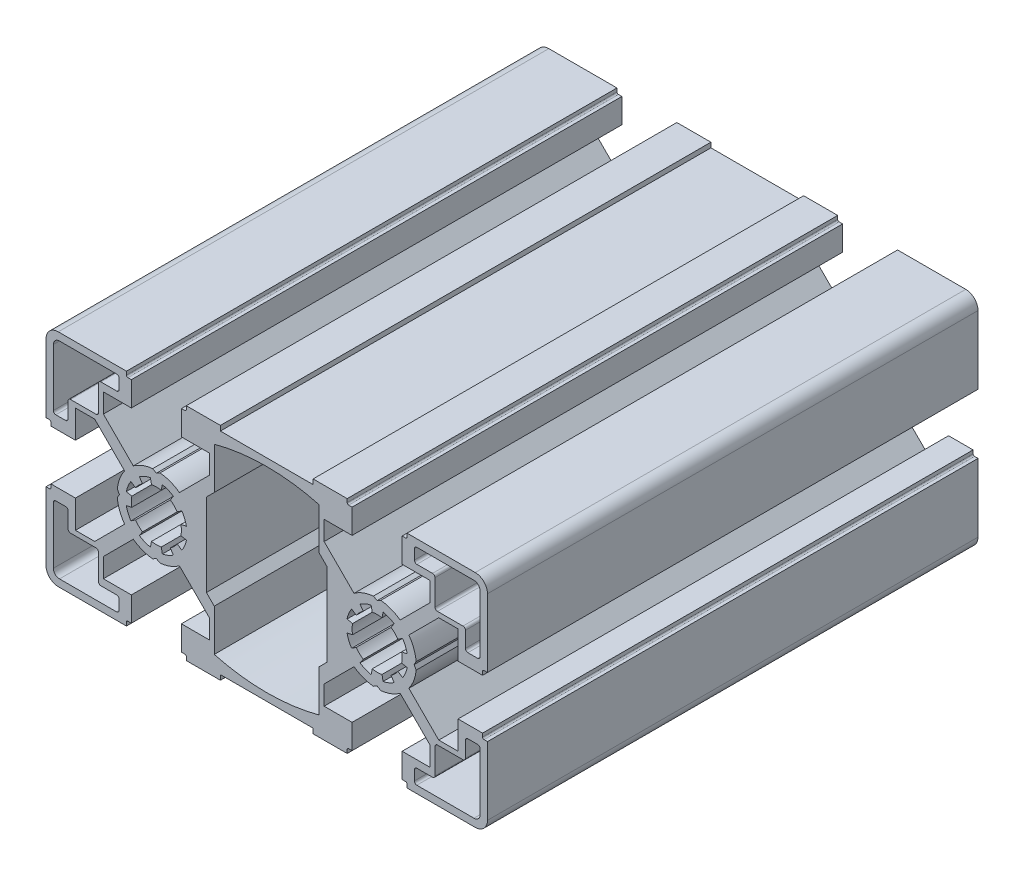
SolidWorks part; units mm, degrees
ref_plane "前视基准面" through (0, 0, 0) normal (0, 0, 1) x (1, 0, 0)
ref_plane "上视基准面" through (0, 0, 0) normal (0, 1, 0) x (1, 0, 0)
ref_plane "右视基准面" through (0, 0, 0) normal (1, 0, 0) x (0, 0, -1)
sketch "草图1" plane through (0, 0, 0) normal (0, 0, 1) x (1, 0, 0)
  line L0 (-29.0828, 22.0458) -> (-42.9828, 22.0458)
  line L1 (-45.4828, 19.5458) -> (-45.4828, 5.6458)
  line L2 (-28.0828, 16.0458) -> (-33.7828, 16.0458)
  line L3 (-39.4828, 10.3458) -> (-39.4828, 4.6458)
  line L4 (-43.4828, 7.1458) -> (-41.4828, 7.1458)
  line L5 (-40.9828, 7.6458) -> (-40.9828, 10.8458)
  line L6 (-40.4828, 11.3458) -> (-35.2828, 11.3458)
  line L7 (-34.7828, 11.8458) -> (-34.7828, 17.0458)
  line L8 (-34.2828, 17.5458) -> (-31.0828, 17.5458)
  line L9 (-30.5828, 18.0458) -> (-30.5828, 20.0458)
  line L10 (-31.0828, 20.5458) -> (-42.7328, 20.5458)
  line L11 (-43.9828, 19.2958) -> (-43.9828, 7.6458)
  line L12 (-28.0828, 21.0458) -> (-28.7828, 21.0458)
  line L13 (-29.0828, 21.3458) -> (-29.0828, 22.0458)
  line L14 (-45.4828, 5.6458) -> (-44.7828, 5.6458)
  line L15 (-44.4828, 5.3458) -> (-44.4828, 4.6458)
  line L16 (-39.4828, 10.3458) -> (-35.5506, 10.3458)
  line L17 (-44.4828, 4.6458) -> (-42.5828, 4.6458)
  line L18 (-41.3828, 4.6458) -> (-39.4828, 4.6458)
  line L19 (-33.7828, 16.0458) -> (-33.7828, 12.1136)
  line L20 (-28.0828, 21.0458) -> (-28.0828, 19.1458)
  line L21 (-28.0828, 17.9458) -> (-28.0828, 16.0458)
  line L22 (-35.5506, 10.3458) -> (-29.4541, 4.2493)
  line L23 (-33.7828, 12.1136) -> (-27.6863, 6.0171)
  line L24 (-16.8828, 22.0458) -> (-9.9328, 22.0458)
  line L25 (-9.9328, 21.0458) -> (8.9672, 21.0458)
  line L26 (-17.8828, 16.0458) -> (-12.1828, 16.0458)
  line L27 (-17.8828, 21.0458) -> (-17.1828, 21.0458)
  line L28 (-16.8828, 21.3458) -> (-16.8828, 22.0458)
  line L29 (-12.1828, 16.0458) -> (-12.1828, 12.1136)
  line L30 (-11.1828, 9.578) -> (-12.7828, 7.978)
  line L31 (-12.1828, 12.1136) -> (-18.2793, 6.0171)
  line L32 (-17.8828, 21.0458) -> (-17.8828, 19.1458)
  line L33 (-17.8828, 17.6208) -> (-17.8828, 16.0458)
  line L34 (-29.0828, -22.9542) -> (-42.9828, -22.9542)
  line L35 (-45.4828, -20.4542) -> (-45.4828, -6.5542)
  line L36 (-28.0828, -16.9542) -> (-33.7828, -16.9542)
  line L37 (-39.4828, -11.2542) -> (-39.4828, -5.5542)
  line L38 (-43.4828, -8.0542) -> (-41.4828, -8.0542)
  line L39 (-40.9828, -8.5542) -> (-40.9828, -11.7542)
  line L40 (-40.4828, -12.2542) -> (-35.2828, -12.2542)
  line L41 (-34.7828, -12.7542) -> (-34.7828, -17.9542)
  line L42 (-34.2828, -18.4542) -> (-31.0828, -18.4542)
  line L43 (-30.5828, -18.9542) -> (-30.5828, -20.9542)
  line L44 (-31.0828, -21.4542) -> (-42.7328, -21.4542)
  line L45 (-43.9828, -20.2042) -> (-43.9828, -8.5542)
  line L46 (-28.0828, -21.9542) -> (-28.7828, -21.9542)
  line L47 (-29.0828, -22.2542) -> (-29.0828, -22.9542)
  line L48 (-45.4828, -6.5542) -> (-44.7828, -6.5542)
  line L49 (-44.4828, -6.2542) -> (-44.4828, -5.5542)
  line L50 (-39.4828, -11.2542) -> (-35.5506, -11.2542)
  line L51 (-44.4828, -5.5542) -> (-42.5828, -5.5542)
  line L52 (-41.3828, -5.5542) -> (-39.4828, -5.5542)
  line L53 (-33.7828, -16.9542) -> (-33.7828, -13.022)
  line L54 (-28.0828, -21.9542) -> (-28.0828, -20.0542)
  line L55 (-28.0828, -18.8542) -> (-28.0828, -16.9542)
  line L56 (-35.5506, -11.2542) -> (-29.4541, -5.1577)
  line L57 (-33.7828, -13.022) -> (-27.6863, -6.9255)
  line L58 (-17.8828, -16.9542) -> (-12.1828, -16.9542)
  line L59 (-17.8828, -21.9542) -> (-17.1828, -21.9542)
  line L60 (-16.8828, -22.2542) -> (-16.8828, -22.9542)
  line L61 (-12.1828, -16.9542) -> (-12.1828, -13.022)
  line L62 (-11.1828, -10.4864) -> (-12.7828, -8.8864)
  line L63 (-12.1828, -13.022) -> (-18.2793, -6.9255)
  line L64 (-17.8828, -21.9542) -> (-17.8828, -20.0542)
  line L65 (-17.8828, -18.8542) -> (-17.8828, -16.9542)
  line L66 (-26.4551, -5.6509) -> (-25.8162, -4.6947)
  line L67 (-24.2021, -6.5841) -> (-23.9778, -5.4562)
  line L68 (-21.7635, -6.5841) -> (-21.9878, -5.4562)
  line L69 (-19.5105, -5.6509) -> (-20.1494, -4.6947)
  line L70 (-17.7861, -3.9265) -> (-18.7423, -3.2876)
  line L71 (-16.8529, -1.6735) -> (-17.9808, -1.4492)
  line L72 (-16.8529, 0.7651) -> (-17.9808, 0.5408)
  line L73 (-17.7861, 3.0181) -> (-18.7423, 2.3792)
  line L74 (-19.5105, 4.7425) -> (-20.1494, 3.7863)
  line L75 (-21.7635, 5.6757) -> (-21.9878, 4.5478)
  line L76 (-24.2021, 5.6757) -> (-23.9778, 4.5478)
  line L77 (-26.4551, 4.7425) -> (-25.8162, 3.7863)
  line L78 (-28.1795, 3.0181) -> (-27.2233, 2.3792)
  line L79 (-29.1127, 0.7651) -> (-27.9848, 0.5408)
  line L80 (-29.1127, -1.6735) -> (-27.9848, -1.4492)
  line L81 (-28.1795, -3.9265) -> (-27.2233, -3.2876)
  line L82 (-22.9828, 7.0775) -> (-22.2328, 7.5106)
  line L83 (-22.9828, 7.0775) -> (-23.7328, 7.5106)
  line L84 (-22.9828, -7.986) -> (-22.2328, -8.419)
  line L85 (-22.9828, -7.986) -> (-23.7328, -8.419)
  line L86 (-30.5146, -0.4542) -> (-30.9476, -1.2042)
  line L87 (-30.5146, -0.4542) -> (-30.9476, 0.2958)
  line L88 (15.9172, 22.0458) -> (8.9672, 22.0458)
  line L89 (16.9172, 16.0458) -> (11.2172, 16.0458)
  line L90 (16.9172, 21.0458) -> (16.2172, 21.0458)
  line L91 (15.9172, 21.3458) -> (15.9172, 22.0458)
  line L92 (11.2172, 16.0458) -> (11.2172, 12.1136)
  line L93 (16.9172, 21.0458) -> (16.9172, 19.1458)
  line L94 (16.9172, 17.9458) -> (16.9172, 16.0458)
  line L95 (10.2172, 9.578) -> (11.8172, 7.978)
  line L96 (11.2172, 12.1136) -> (17.3137, 6.0171)
  line L97 (28.1172, 22.0458) -> (42.0172, 22.0458)
  line L98 (44.5172, 19.5458) -> (44.5172, 5.6458)
  line L99 (27.1172, 16.0458) -> (32.8172, 16.0458)
  line L100 (38.5172, 10.3458) -> (38.5172, 4.6458)
  line L101 (42.5172, 7.1458) -> (40.5172, 7.1458)
  line L102 (40.0172, 7.6458) -> (40.0172, 10.8458)
  line L103 (39.5172, 11.3458) -> (34.3172, 11.3458)
  line L104 (33.8172, 11.8458) -> (33.8172, 17.0458)
  line L105 (33.3172, 17.5458) -> (30.1172, 17.5458)
  line L106 (29.6172, 18.0458) -> (29.6172, 20.0458)
  line L107 (30.1172, 20.5458) -> (41.7672, 20.5458)
  line L108 (43.0172, 19.2958) -> (43.0172, 7.6458)
  line L109 (27.1172, 21.0458) -> (27.8172, 21.0458)
  line L110 (28.1172, 21.3458) -> (28.1172, 22.0458)
  line L111 (44.5172, 5.6458) -> (43.8172, 5.6458)
  line L112 (43.5172, 5.3458) -> (43.5172, 4.6458)
  line L113 (38.5172, 10.3458) -> (34.585, 10.3458)
  line L114 (43.5172, 4.6458) -> (41.6172, 4.6458)
  line L115 (40.4172, 4.6458) -> (38.5172, 4.6458)
  line L116 (32.8172, 16.0458) -> (32.8172, 12.1136)
  line L117 (34.585, 10.3458) -> (28.4884, 4.2493)
  line L118 (32.8172, 12.1136) -> (26.7207, 6.0171)
  line L119 (27.1172, 21.0458) -> (27.1172, 19.1458)
  line L120 (27.1172, 17.9458) -> (27.1172, 16.0458)
  line L121 (16.9172, -16.9542) -> (11.2172, -16.9542)
  line L122 (16.9172, -21.9542) -> (16.2172, -21.9542)
  line L123 (15.9172, -22.2542) -> (15.9172, -22.9542)
  line L124 (11.2172, -16.9542) -> (11.2172, -13.022)
  line L125 (16.9172, -21.9542) -> (16.9172, -20.0542)
  line L126 (16.9172, -18.8542) -> (16.9172, -16.9542)
  line L127 (10.2172, -10.4864) -> (11.8172, -8.8864)
  line L128 (11.2172, -13.022) -> (17.3137, -6.9255)
  line L129 (28.1172, -22.9542) -> (42.0172, -22.9542)
  line L130 (44.5172, -20.4542) -> (44.5172, -6.5542)
  line L131 (27.1172, -16.9542) -> (32.8172, -16.9542)
  line L132 (38.5172, -11.2542) -> (38.5172, -5.5542)
  line L133 (40.0172, -8.5542) -> (40.0172, -11.7542)
  line L134 (39.5172, -12.2542) -> (34.3172, -12.2542)
  line L135 (33.8172, -12.7542) -> (33.8172, -17.9542)
  line L136 (33.3172, -18.4542) -> (30.1172, -18.4542)
  line L137 (29.6172, -18.9542) -> (29.6172, -20.9542)
  line L138 (30.1172, -21.4542) -> (41.7672, -21.4542)
  line L139 (43.0172, -20.2042) -> (43.0172, -8.5542)
  line L140 (27.1172, -21.9542) -> (27.8172, -21.9542)
  line L141 (28.1172, -22.2542) -> (28.1172, -22.9542)
  line L142 (44.5172, -6.5542) -> (43.8172, -6.5542)
  line L143 (43.5172, -6.2542) -> (43.5172, -5.5542)
  line L144 (38.5172, -11.2542) -> (34.585, -11.2542)
  line L145 (43.5172, -5.5542) -> (41.6172, -5.5542)
  line L146 (40.4172, -5.5542) -> (38.5172, -5.5542)
  line L147 (32.8172, -16.9542) -> (32.8172, -13.022)
  line L148 (34.585, -11.2542) -> (28.4884, -5.1577)
  line L149 (32.8172, -13.022) -> (26.7207, -6.9255)
  line L150 (27.1172, -21.9542) -> (27.1172, -20.0542)
  line L151 (27.1172, -18.8542) -> (27.1172, -16.9542)
  line L152 (18.5449, -5.6509) -> (19.1838, -4.6947)
  line L153 (20.7979, -6.5841) -> (21.0222, -5.4562)
  line L154 (23.2365, -6.5841) -> (23.0122, -5.4562)
  line L155 (25.4895, -5.6509) -> (24.8506, -4.6947)
  line L156 (27.2139, -3.9265) -> (26.2577, -3.2876)
  line L157 (28.1471, -1.6735) -> (27.0192, -1.4492)
  line L158 (28.1471, 0.7651) -> (27.0192, 0.5408)
  line L159 (27.2139, 3.0181) -> (26.2577, 2.3792)
  line L160 (25.4895, 4.7425) -> (24.8506, 3.7863)
  line L161 (23.2365, 5.6757) -> (23.0122, 4.5478)
  line L162 (20.7979, 5.6757) -> (21.0222, 4.5478)
  line L163 (18.5449, 4.7425) -> (19.1838, 3.7863)
  line L164 (16.8205, 3.0181) -> (17.7767, 2.3792)
  line L165 (15.8873, 0.7651) -> (17.0152, 0.5408)
  line L166 (15.8873, -1.6735) -> (17.0152, -1.4492)
  line L167 (16.8205, -3.9265) -> (17.7767, -3.2876)
  line L168 (22.0172, 7.0775) -> (22.7672, 7.5106)
  line L169 (22.0172, 7.0775) -> (21.2672, 7.5106)
  line L170 (22.0172, -7.986) -> (22.7672, -8.419)
  line L171 (22.0172, -7.986) -> (21.2672, -8.419)
  line L172 (29.5489, -0.4542) -> (29.982, -1.2042)
  line L173 (29.5489, -0.4542) -> (29.982, 0.2958)
  line L174 (-11.1828, 9.578) -> (-11.1828, 18.1066)
  line L175 (-11.1828, -10.4864) -> (-11.1828, -19.015)
  line L176 (10.2172, -10.4864) -> (10.2172, -19.015)
  line L177 (10.2172, 9.578) -> (10.2172, 18.1066)
  line L178 (-16.8828, -22.9542) -> (-9.9328, -22.9542)
  line L179 (8.9672, -22.9542) -> (15.9172, -22.9542)
  line L180 (-9.9328, -21.9542) -> (8.9672, -21.9542)
  line L181 (8.9672, -22.9542) -> (8.9672, -21.9542)
  line L182 (8.9672, 21.0458) -> (8.9672, 22.0458)
  line L183 (-9.9328, -22.9542) -> (-9.9328, -21.9542)
  line L184 (-9.9328, 21.0458) -> (-9.9328, 22.0458)
  line L185 (-12.7828, 7.978) -> (-12.7828, -8.8864)
  line L186 (11.8172, 7.978) -> (11.8172, -8.8864)
  line L187 (40.5172, -8.0542) -> (42.5172, -8.0542)
  line L188 (-28.0828, -18.8542) -> (-28.0828, -20.0542)
  line L189 (-17.8828, -18.8542) -> (-17.8828, -20.0542)
  line L190 (16.9172, -18.8542) -> (16.9172, -20.0542)
  line L191 (27.1172, -18.8542) -> (27.1172, -20.0542)
  line L192 (40.4172, -5.5542) -> (41.6172, -5.5542)
  line L193 (40.4172, 4.6458) -> (41.6172, 4.6458)
  line L194 (27.1172, 17.9458) -> (27.1172, 19.1458)
  line L195 (16.9172, 17.9458) -> (16.9172, 19.1458)
  line L196 (-17.8828, 17.6208) -> (-17.8828, 19.1458)
  line L197 (-28.0828, 17.9458) -> (-28.0828, 19.1458)
  line L198 (-41.3828, 4.6458) -> (-42.5828, 4.6458)
  line L199 (-42.5828, -5.5542) -> (-41.3828, -5.5542)
  arc A0 (-42.9828, 22.0458) -> (-45.4828, 19.5458) centre (-42.9828, 19.5458) ccw
  arc A1 (-41.4828, 7.1458) -> (-40.9828, 7.6458) centre (-41.4828, 7.6458) ccw
  arc A2 (-40.4828, 11.3458) -> (-40.9828, 10.8458) centre (-40.4828, 10.8458) ccw
  arc A3 (-35.2828, 11.3458) -> (-34.7828, 11.8458) centre (-35.2828, 11.8458) ccw
  arc A4 (-34.2828, 17.5458) -> (-34.7828, 17.0458) centre (-34.2828, 17.0458) ccw
  arc A5 (-31.0828, 17.5458) -> (-30.5828, 18.0458) centre (-31.0828, 18.0458) ccw
  arc A6 (-30.5828, 20.0458) -> (-31.0828, 20.5458) centre (-31.0828, 20.0458) ccw
  arc A7 (-42.7328, 20.5458) -> (-43.9828, 19.2958) centre (-42.7328, 19.2958) ccw
  arc A8 (-43.9828, 7.6458) -> (-43.4828, 7.1458) centre (-43.4828, 7.6458) ccw
  arc A9 (-29.0828, 21.3458) -> (-28.7828, 21.0458) centre (-28.7828, 21.3458) ccw
  arc A10 (-44.4828, 5.3458) -> (-44.7828, 5.6458) centre (-44.7828, 5.3458) ccw
  arc A11 (-27.2233, -3.2876) -> (-25.8162, -4.6947) centre (-22.9828, -0.4542) ccw
  arc A12 (-23.9778, -5.4562) -> (-21.9878, -5.4562) centre (-22.9828, -0.4542) ccw
  arc A13 (-20.1494, -4.6947) -> (-18.7423, -3.2876) centre (-22.9828, -0.4542) ccw
  arc A14 (-17.9808, -1.4492) -> (-17.9808, 0.5408) centre (-22.9828, -0.4542) ccw
  arc A15 (-18.7423, 2.3792) -> (-20.1494, 3.7863) centre (-22.9828, -0.4542) ccw
  arc A16 (-21.9878, 4.5478) -> (-23.9778, 4.5478) centre (-22.9828, -0.4542) ccw
  arc A17 (-25.8162, 3.7863) -> (-27.2233, 2.3792) centre (-22.9828, -0.4542) ccw
  arc A18 (-27.9848, 0.5408) -> (-27.9848, -1.4492) centre (-22.9828, -0.4542) ccw
  arc A19 (-26.4551, -5.6509) -> (-24.2021, -6.5841) centre (-22.9828, -0.4542) ccw
  arc A20 (-21.7635, -6.5841) -> (-19.5105, -5.6509) centre (-22.9828, -0.4542) ccw
  arc A21 (-17.7861, -3.9265) -> (-16.8529, -1.6735) centre (-22.9828, -0.4542) ccw
  arc A22 (-16.8529, 0.7651) -> (-17.7861, 3.0181) centre (-22.9828, -0.4542) ccw
  arc A23 (-19.5105, 4.7425) -> (-21.7635, 5.6757) centre (-22.9828, -0.4542) ccw
  arc A24 (-24.2021, 5.6757) -> (-26.4551, 4.7425) centre (-22.9828, -0.4542) ccw
  arc A25 (-28.1795, 3.0181) -> (-29.1127, 0.7651) centre (-22.9828, -0.4542) ccw
  arc A26 (-29.1127, -1.6735) -> (-28.1795, -3.9265) centre (-22.9828, -0.4542) ccw
  arc A27 (-29.4541, 4.2493) -> (-30.9476, 0.2958) centre (-22.9828, -0.4542) ccw
  arc A28 (-30.9476, -1.2042) -> (-29.4541, -5.1577) centre (-22.9828, -0.4542) ccw
  arc A29 (-27.6863, -6.9255) -> (-23.7328, -8.419) centre (-22.9828, -0.4542) ccw
  arc A30 (-22.2328, -8.419) -> (-18.2793, -6.9255) centre (-22.9828, -0.4542) ccw
  arc A31 (-18.2793, 6.0171) -> (-22.2328, 7.5106) centre (-22.9828, -0.4542) ccw
  arc A32 (-23.7328, 7.5106) -> (-27.6863, 6.0171) centre (-22.9828, -0.4542) ccw
  arc A33 (-17.1828, 21.0458) -> (-16.8828, 21.3458) centre (-17.1828, 21.3458) ccw
  arc A34 (-45.4828, -20.4542) -> (-42.9828, -22.9542) centre (-42.9828, -20.4542) ccw
  arc A35 (-40.9828, -8.5542) -> (-41.4828, -8.0542) centre (-41.4828, -8.5542) ccw
  arc A36 (-40.9828, -11.7542) -> (-40.4828, -12.2542) centre (-40.4828, -11.7542) ccw
  arc A37 (-34.7828, -12.7542) -> (-35.2828, -12.2542) centre (-35.2828, -12.7542) ccw
  arc A38 (-34.7828, -17.9542) -> (-34.2828, -18.4542) centre (-34.2828, -17.9542) ccw
  arc A39 (-30.5828, -18.9542) -> (-31.0828, -18.4542) centre (-31.0828, -18.9542) ccw
  arc A40 (-31.0828, -21.4542) -> (-30.5828, -20.9542) centre (-31.0828, -20.9542) ccw
  arc A41 (-43.9828, -20.2042) -> (-42.7328, -21.4542) centre (-42.7328, -20.2042) ccw
  arc A42 (-43.4828, -8.0542) -> (-43.9828, -8.5542) centre (-43.4828, -8.5542) ccw
  arc A43 (-28.7828, -21.9542) -> (-29.0828, -22.2542) centre (-28.7828, -22.2542) ccw
  arc A44 (-44.7828, -6.5542) -> (-44.4828, -6.2542) centre (-44.7828, -6.2542) ccw
  arc A45 (-16.8828, -22.2542) -> (-17.1828, -21.9542) centre (-17.1828, -22.2542) ccw
  arc A46 (15.9172, 21.3458) -> (16.2172, 21.0458) centre (16.2172, 21.3458) ccw
  arc A47 (17.7767, -3.2876) -> (19.1838, -4.6947) centre (22.0172, -0.4542) ccw
  arc A48 (21.0222, -5.4562) -> (23.0122, -5.4562) centre (22.0172, -0.4542) ccw
  arc A49 (24.8506, -4.6947) -> (26.2577, -3.2876) centre (22.0172, -0.4542) ccw
  arc A50 (27.0192, -1.4492) -> (27.0192, 0.5408) centre (22.0172, -0.4542) ccw
  arc A51 (26.2577, 2.3792) -> (24.8506, 3.7863) centre (22.0172, -0.4542) ccw
  arc A52 (23.0122, 4.5478) -> (21.0222, 4.5478) centre (22.0172, -0.4542) ccw
  arc A53 (19.1838, 3.7863) -> (17.7767, 2.3792) centre (22.0172, -0.4542) ccw
  arc A54 (17.0152, 0.5408) -> (17.0152, -1.4492) centre (22.0172, -0.4542) ccw
  arc A55 (18.5449, -5.6509) -> (20.7979, -6.5841) centre (22.0172, -0.4542) ccw
  arc A56 (23.2365, -6.5841) -> (25.4895, -5.6509) centre (22.0172, -0.4542) ccw
  arc A57 (27.2139, -3.9265) -> (28.1471, -1.6735) centre (22.0172, -0.4542) ccw
  arc A58 (28.1471, 0.7651) -> (27.2139, 3.0181) centre (22.0172, -0.4542) ccw
  arc A59 (25.4895, 4.7425) -> (23.2365, 5.6757) centre (22.0172, -0.4542) ccw
  arc A60 (20.7979, 5.6757) -> (18.5449, 4.7425) centre (22.0172, -0.4542) ccw
  arc A61 (16.8205, 3.0181) -> (15.8873, 0.7651) centre (22.0172, -0.4542) ccw
  arc A62 (15.8873, -1.6735) -> (16.8205, -3.9265) centre (22.0172, -0.4542) ccw
  arc A63 (17.3137, -6.9255) -> (21.2672, -8.419) centre (22.0172, -0.4542) ccw
  arc A64 (22.7672, -8.419) -> (26.7207, -6.9255) centre (22.0172, -0.4542) ccw
  arc A65 (28.4884, -5.1577) -> (29.982, -1.2042) centre (22.0172, -0.4542) ccw
  arc A66 (29.982, 0.2958) -> (28.4884, 4.2493) centre (22.0172, -0.4542) ccw
  arc A67 (26.7207, 6.0171) -> (22.7672, 7.5106) centre (22.0172, -0.4542) ccw
  arc A68 (21.2672, 7.5106) -> (17.3137, 6.0171) centre (22.0172, -0.4542) ccw
  arc A69 (44.5172, 19.5458) -> (42.0172, 22.0458) centre (42.0172, 19.5458) ccw
  arc A70 (40.0172, 7.6458) -> (40.5172, 7.1458) centre (40.5172, 7.6458) ccw
  arc A71 (40.0172, 10.8458) -> (39.5172, 11.3458) centre (39.5172, 10.8458) ccw
  arc A72 (33.8172, 11.8458) -> (34.3172, 11.3458) centre (34.3172, 11.8458) ccw
  arc A73 (33.8172, 17.0458) -> (33.3172, 17.5458) centre (33.3172, 17.0458) ccw
  arc A74 (29.6172, 18.0458) -> (30.1172, 17.5458) centre (30.1172, 18.0458) ccw
  arc A75 (30.1172, 20.5458) -> (29.6172, 20.0458) centre (30.1172, 20.0458) ccw
  arc A76 (43.0172, 19.2958) -> (41.7672, 20.5458) centre (41.7672, 19.2958) ccw
  arc A77 (42.5172, 7.1458) -> (43.0172, 7.6458) centre (42.5172, 7.6458) ccw
  arc A78 (27.8172, 21.0458) -> (28.1172, 21.3458) centre (27.8172, 21.3458) ccw
  arc A79 (43.8172, 5.6458) -> (43.5172, 5.3458) centre (43.8172, 5.3458) ccw
  arc A80 (16.2172, -21.9542) -> (15.9172, -22.2542) centre (16.2172, -22.2542) ccw
  arc A81 (42.0172, -22.9542) -> (44.5172, -20.4542) centre (42.0172, -20.4542) ccw
  arc A82 (40.5172, -8.0542) -> (40.0172, -8.5542) centre (40.5172, -8.5542) ccw
  arc A83 (39.5172, -12.2542) -> (40.0172, -11.7542) centre (39.5172, -11.7542) ccw
  arc A84 (34.3172, -12.2542) -> (33.8172, -12.7542) centre (34.3172, -12.7542) ccw
  arc A85 (33.3172, -18.4542) -> (33.8172, -17.9542) centre (33.3172, -17.9542) ccw
  arc A86 (30.1172, -18.4542) -> (29.6172, -18.9542) centre (30.1172, -18.9542) ccw
  arc A87 (29.6172, -20.9542) -> (30.1172, -21.4542) centre (30.1172, -20.9542) ccw
  arc A88 (41.7672, -21.4542) -> (43.0172, -20.2042) centre (41.7672, -20.2042) ccw
  arc A89 (43.0172, -8.5542) -> (42.5172, -8.0542) centre (42.5172, -8.5542) ccw
  arc A90 (28.1172, -22.2542) -> (27.8172, -21.9542) centre (27.8172, -22.2542) ccw
  arc A91 (43.5172, -6.2542) -> (43.8172, -6.5542) centre (43.8172, -6.2542) ccw
  arc A92 (10.2172, 18.1066) -> (-11.1828, 18.1066) centre (-0.4828, -21.9542) ccw
  arc A93 (-11.1828, -19.015) -> (10.2172, -19.015) centre (-0.4828, 21.0458) ccw
extrude "凸台-拉伸1" add sketch "草图1" along normal blind 100
